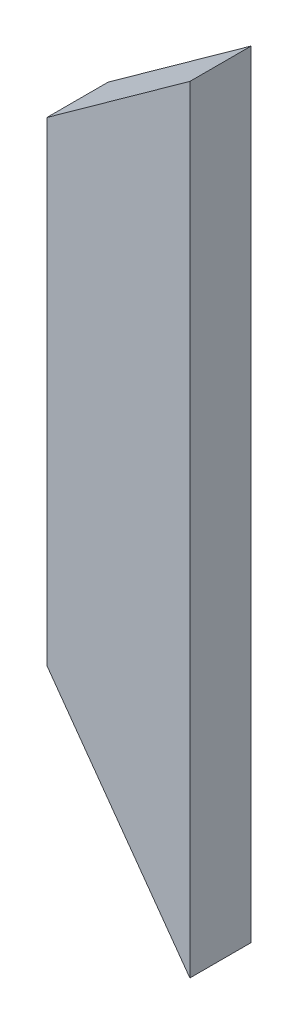
SolidWorks part; units mm, degrees
material "Balsa"
ref_plane "Front Plane" through (0, 0, 0) normal (0, 0, 1) x (1, 0, 0)
ref_plane "Top Plane" through (0, 0, 0) normal (0, 1, 0) x (1, 0, 0)
ref_plane "Right Plane" through (0, 0, 0) normal (1, 0, 0) x (0, 0, -1)
sketch "Sketch1" plane through (0, 0, 0) normal (0, 0, 1) x (1, 0, 0)
  line L0 (44.45, 241.3) -> (-44.45, 177.4146)
  line L1 (-44.45, 241.3) -> (44.45, 241.3)
  line L2 (-44.45, 241.3) -> (-44.45, -241.3)
  line L3 (-44.45, -241.3) -> (44.45, -241.3)
  line L4 (44.45, 241.3) -> (44.45, -241.3)
  line L5 (-44.45, 241.3) -> (44.45, -241.3) construction
  line L6 (-44.45, -241.3) -> (44.45, 241.3) construction
  line L7 (44.45, -241.3) -> (-44.45, -117.5157)
  point P0 (0, 0)
  dimension "D1" = 482.6
  dimension "D2" = 88.9
  dimension "D3" = 109.474
  dimension "D4" = 152.4
extrude "Boss-Extrude1" add sketch "Sketch1" along normal blind 38.1
